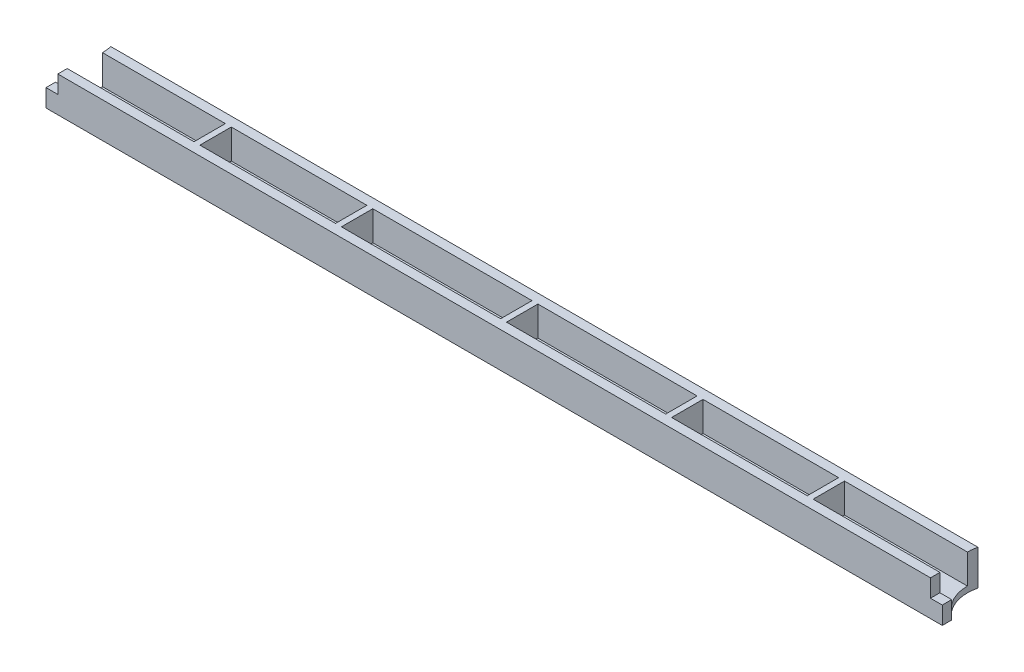
SolidWorks part; units mm, degrees
ref_plane "Front Plane" through (0, 0, 0) normal (0, 0, 1) x (1, 0, 0)
ref_plane "Top Plane" through (0, 0, 0) normal (0, 1, 0) x (1, 0, 0)
ref_plane "Right Plane" through (0, 0, 0) normal (1, 0, 0) x (0, 0, -1)
sketch "Sketch2" plane through (0, 0, 0) normal (0, 0, 1) x (1, 0, 0)
  line L1 (0, 0) -> (120.65, 0)
  line L2 (0, 0) -> (0, 9.525)
  line L3 (0, 9.525) -> (120.65, 9.525)
  line L4 (120.65, 0) -> (120.65, 9.525)
  point P2 (0, 9.525)
  point P7 (0.2218, 9.525)
  point P8 (5.4993, 9.525)
  point P9 (5.441, 9.2885)
  dimension "D1" = 120.65
  dimension "D2" = 9.525
extrude "Boss-Extrude1" add sketch "Sketch2" along normal blind 2.54
sketch "Sketch4" plane through (0, 0, 0) normal (-1, 0, 0) x (0, 0, 1)
  line L0 (2.54, 0) -> (0, 0) construction
  line L1 (0, 1.5875) -> (13.5255, 1.5875)
  line L2 (0, 1.5875) -> (0, 0)
  line L3 (0, 0) -> (13.5255, 0)
  line L4 (13.5255, 1.5875) -> (13.5255, 0)
  line L5 (1.27, 9.525) -> (1.27, 0) construction
  line L6 (2.54, 9.525) -> (0, 9.525) construction
  line L7 (0, 9.525) -> (0, 0) construction
  dimension "D1" = 1.5875
  dimension "D2" = 13.5255
extrude "Boss-Extrude2" add sketch "Sketch4" against normal up to surface (120.65 mm away) up to face at (120.65, 4.7625, 1.27)
sketch "Sketch13" plane through (0, 1.5875, 0) normal (0, 1, 0) x (1, 0, 0)
  line L0 (120.65, -2.54) -> (120.65, -13.5255) construction
  line L1 (0, -13.5255) -> (120.65, -13.5255)
  line L2 (0, -13.5255) -> (0, -10.9855)
  line L3 (0, -10.9855) -> (120.65, -10.9855)
  line L4 (120.65, -13.5255) -> (120.65, -10.9855)
  dimension "D1" = 2.54
extrude "Boss-Extrude3" add sketch "Sketch13" along normal blind 7.9375
sketch "Sketch6" plane through (0, 0, 0) normal (0, 1, 0) x (1, 0, 0)
  line L0 (-1000, -6.7627) -> (49000, -6.7627) construction
  line L3 (31.75, -6.7627) -> (12.7, -6.7628) construction
  line L5 (0, -10.9855) -> (0, -2.54) construction
  line L8 (0, -10.9855) -> (0, -2.54) construction
  point P9 (0, -6.7627)
  dimension "D1" = 19.05
  dimension "D2" = 12.7
sketch "Sketch11" plane through (0, 1.5875, 0) normal (0, 1, 0) x (1, 0, 0)
  line L0 (117.475, -6.7627) -> (-49882.525, -6.7628) construction
  line L1 (120.65, -2.54) -> (120.65, -10.9855) construction
  line L2 (63.5, -6.7628) -> (44.45, -6.7628) construction
  line L3 (63.5, -8.6614) -> (44.45, -8.6614)
  line L4 (63.5, -4.8641) -> (44.45, -4.8641)
  arc A0 (63.5, -8.6614) -> (63.5, -4.8641) centre (63.5, -6.7628) ccw
  arc A1 (44.45, -4.8641) -> (44.45, -8.6614) centre (44.45, -6.7628) ccw
  point P4 (120.65, -6.7627)
  point P7 (53.975, -6.7628)
  dimension "D1" = 3.7973
  dimension "D2" = 57.15
  dimension "D3" = 19.05
extrude "Cut-Extrude4" cut sketch "Sketch11" against normal through all
hole_wizard "#6 Clearance Hole1" positions "Sketch7" profile "Sketch8" hole size "#6" standard "ANSI Inch" end condition through all
sketch "Sketch7" plane through (0, 0, 0) normal (0, 1, 0) x (1, 0, 0)
  line L0 (-882.525, -6.7627) -> (49117.475, -6.7627) construction
  line L1 (120.65, -2.54) -> (120.65, -10.9855) construction
  point P3 (31.75, -6.7627)
  point P9 (12.7, -6.7628)
  point P22 (120.65, -6.7627)
  point P25 (107.95, -6.7627)
  dimension "D1" = 12.7
sketch "Sketch8" plane through (31.75, 0, 6.7627) normal (1, 0, 0) x (0, 0, -1)
  line L0 (0, 0) -> (0, 9.525)
  line L1 (0, 9.525) -> (2.1526, 9.525)
  line L2 (2.1526, 9.525) -> (2.1526, 0)
  line L5 (2.1526, 0) -> (0, 0)
  line L11 (0, -6.35) -> (0, 107.95) construction
  dimension "Thru Hole Dia." = 4.3053
  dimension "Thru Hole Depth" = 9.525
sketch "Sketch15" plane through (0, 1.5875, 0) normal (0, 1, 0) x (1, 0, 0)
  line L0 (120.65, -10.9855) -> (0, -10.9855) construction
  line L1 (37.3062, -2.54) -> (38.8937, -2.54)
  line L2 (37.3062, -2.54) -> (37.3062, -10.9855)
  line L3 (37.3062, -10.9855) -> (38.8937, -10.9855)
  line L4 (38.8937, -2.54) -> (38.8937, -10.9855)
  line L5 (37.3062, -2.54) -> (38.8937, -10.9855) construction
  line L6 (37.3062, -10.9855) -> (38.8937, -2.54) construction
  line L7 (120.65, -10.9855) -> (0, -10.9855) construction
  line L8 (75.4063, -2.54) -> (76.9938, -2.54)
  line L9 (75.4063, -2.54) -> (75.4063, -10.9855)
  line L10 (75.4063, -10.9855) -> (76.9938, -10.9855)
  line L11 (76.9938, -2.54) -> (76.9938, -10.9855)
  line L12 (75.4063, -2.54) -> (76.9938, -10.9855) construction
  line L13 (75.4063, -10.9855) -> (76.9938, -2.54) construction
  line L15 (120.65, -2.54) -> (119.8563, -2.54)
  line L16 (120.65, -2.54) -> (120.65, -10.9855)
  line L17 (120.65, -10.9855) -> (119.8563, -10.9855)
  line L18 (119.8563, -2.54) -> (119.8563, -10.9855)
  line L19 (120.65, -2.54) -> (119.8563, -10.9855) construction
  line L20 (120.65, -10.9855) -> (119.8563, -2.54) construction
  line L21 (120.65, -2.54) -> (0, -2.54) construction
  line L22 (34.1312, -2.54) -> (35.7187, -2.54)
  line L23 (34.1312, -2.54) -> (34.1312, -10.9855)
  line L24 (34.1312, -10.9855) -> (35.7187, -10.9855)
  line L25 (35.7187, -2.54) -> (35.7187, -10.9855)
  line L26 (34.1312, -2.54) -> (35.7187, -10.9855) construction
  line L27 (34.1312, -10.9855) -> (35.7187, -2.54) construction
  line L28 (0, -2.54) -> (120.65, -2.54) construction
  line L29 (120.65, -2.54) -> (120.65, -10.9855) construction
  point P0 (38.1, -6.7627)
  point P7 (76.2, -6.7627)
  point P14 (120.2531, -6.7627)
  point P21 (34.925, -6.7627)
  line M13 (0, -10.9855) -> (120.65, -10.9855)
  line M14 (120.65, -10.9855) -> (120.65, -2.54)
  line M15 (120.65, -2.54) -> (0, -2.54)
  dimension "D1" = 1.5875
  dimension "D2" = 0.7937
  dimension "D4" = 6.35
  dimension "D5" = 12.7
extrude "Boss-Extrude4" add sketch "Sketch15" along normal up to surface (7.9375 mm away) contours L4 L2 M15 M13 | L11 L9 M15 M13 | L18 M15 M13 M14 up to face at (60.325, 9.525, 1.27)
sketch "Sketch9" plane through (0, 0, 0) normal (0, 1, 0) x (1, 0, 0)
  circle A3 centre (-6.35, -2.54) radius 10.5664
  circle A4 centre (12.7, -6.7628) radius 2.1526 construction
  dimension "D1" = 19.05
  dimension "D2" = 4.2227
extrude "Cut-Extrude3" cut sketch "Sketch9" against normal through all and the other way through all
sketch "Sketch16" plane through (0, 0, 13.5255) normal (0, 0, 1) x (1, 0, 0)
  line L0 (120.65, 0) -> (0, 0) construction
  line L1 (0, 9.525) -> (3.175, 9.525)
  line L2 (0, 9.525) -> (0, 4.7625)
  line L3 (0, 4.7625) -> (3.175, 4.7625)
  line L4 (3.175, 9.525) -> (3.175, 4.7625)
  dimension "D1" = 3.175
  dimension "D2" = 4.7625
extrude "Cut-Extrude5" cut sketch "Sketch16" against normal up to next
mirror "Mirror1"
